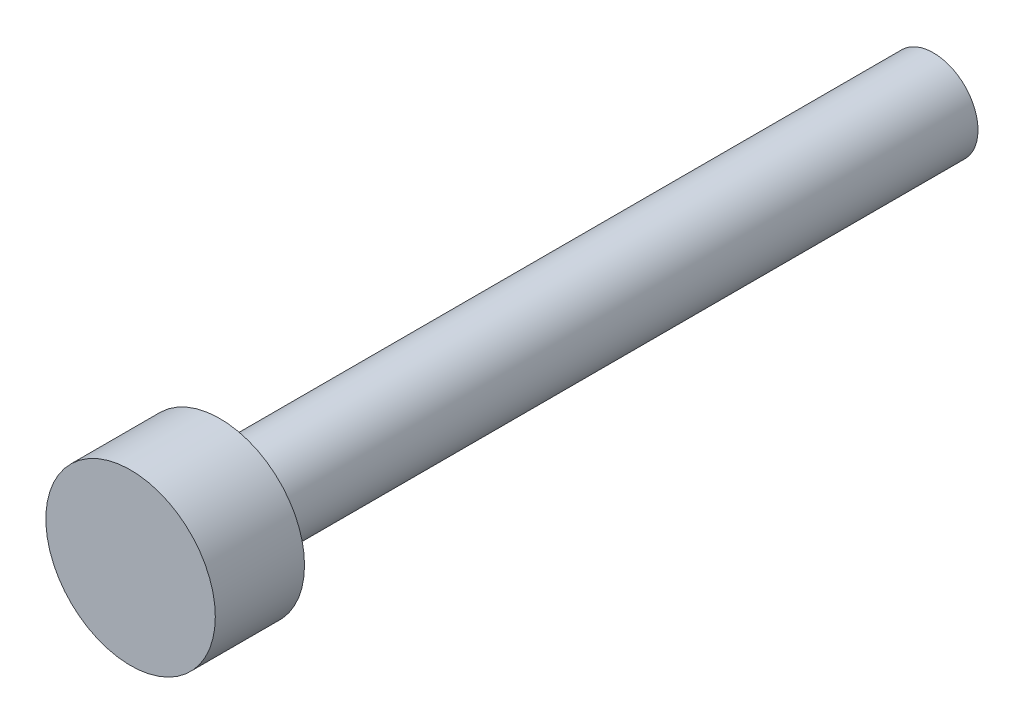
SolidWorks part; units mm, degrees
ref_plane "前视基准面" through (0, 0, 0) normal (0, 0, 1) x (1, 0, 0)
ref_plane "上视基准面" through (0, 0, 0) normal (0, 1, 0) x (1, 0, 0)
ref_plane "右视基准面" through (0, 0, 0) normal (1, 0, 0) x (0, 0, -1)
other "Configuration Table"
sketch "Sketch_Nominal_shank" plane through (0, 0, 0) normal (0, 0, 1) x (1, 0, 0)
  circle A0 centre (0, 0) radius 1
  dimension "D1" = 2
extrude "Nominal_shank" add sketch "Sketch_Nominal_shank" along normal blind 16 from offset 16
sketch "Sketch_Head" plane through (0, 0, 0) normal (0, 0, 1) x (1, 0, 0)
  circle A0 centre (0, 0) radius 1.9
  dimension "D1" = 3.8
extrude "Head" add sketch "Sketch_Head" along normal blind 2 from offset 0
